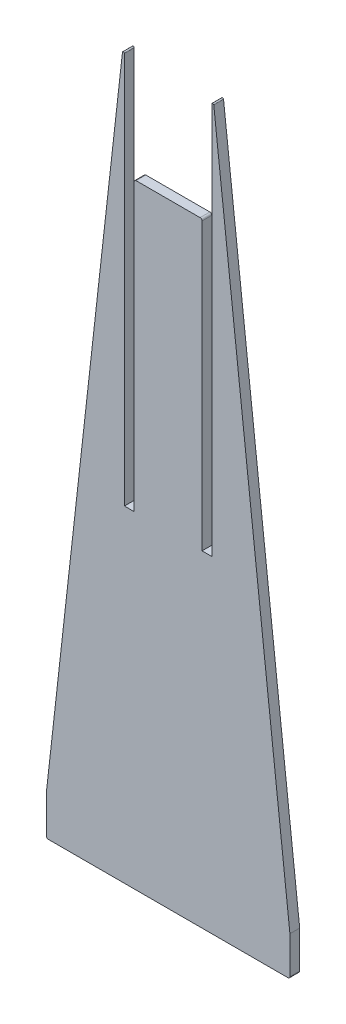
SolidWorks part; units mm, degrees
ref_plane "Front Plane" through (0, 0, 0) normal (0, 0, 1) x (1, 0, 0)
ref_plane "Top Plane" through (0, 0, 0) normal (0, 1, 0) x (1, 0, 0)
ref_plane "Right Plane" through (0, 0, 0) normal (1, 0, 0) x (0, 0, -1)
sketch "Sketch1" plane through (0, 0, 0) normal (0, 0, 1) x (1, 0, 0)
  line L0 (17.35, 0) -> (17.35, 20)
  line L1 (17.35, 0) -> (17.35, 20)
  line L2 (17.35, 20) -> (17.35, 195)
  line L3 (17.35, 20) -> (17.35, 195)
  line L4 (13.75, 450.8) -> (-13.75, 450.8)
  line L5 (-15.75, 448.8) -> (-15.75, 331.2)
  line L6 (-13.75, 329.2) -> (13.75, 329.2)
  line L7 (15.75, 331.2) -> (15.75, 448.8)
  line L8 (13.75, 450.8) -> (-13.75, 450.8)
  line L9 (-15.75, 448.8) -> (-15.75, 331.2)
  line L10 (-13.75, 329.2) -> (13.75, 329.2)
  line L11 (15.75, 331.2) -> (15.75, 448.8)
  line L12 (17.35, 195) -> (17.35, 390)
  line L13 (17.35, 195) -> (17.35, 390)
  line L14 (17.35, 390) -> (17.35, 406.6)
  line L15 (17.35, 390) -> (17.35, 406.6)
  line L16 (17.35, 406.6) -> (22.35, 406.6)
  line L17 (17.35, 406.6) -> (22.35, 406.6)
  line L18 (22.35, 406.6) -> (22.35, 390)
  line L19 (22.35, 406.6) -> (22.35, 390)
  line L20 (22.35, 390) -> (22.35, 195)
  line L21 (22.35, 390) -> (22.35, 195)
  line L22 (22.35, 195) -> (22.35, 20)
  line L23 (22.35, 195) -> (22.35, 20)
  line L24 (22.35, 20) -> (22.35, 0)
  line L25 (22.35, 20) -> (22.35, 0)
  line L26 (22.35, 0) -> (17.35, 0)
  line L27 (22.35, 0) -> (17.35, 0)
  line L28 (-22.35, 0) -> (-22.35, 20)
  line L29 (-22.35, 0) -> (-22.35, 20)
  line L30 (-22.35, 20) -> (-22.35, 195)
  line L31 (-22.35, 20) -> (-22.35, 195)
  line L32 (-22.35, 195) -> (-22.35, 390)
  line L33 (-22.35, 195) -> (-22.35, 390)
  line L34 (-22.35, 390) -> (-22.35, 406.6)
  line L35 (-22.35, 390) -> (-22.35, 406.6)
  line L36 (-22.35, 406.6) -> (-17.35, 406.6)
  line L37 (-22.35, 406.6) -> (-17.35, 406.6)
  line L38 (-17.35, 406.6) -> (-17.35, 390)
  line L39 (-17.35, 406.6) -> (-17.35, 390)
  line L40 (-17.35, 390) -> (-17.35, 195)
  line L41 (-17.35, 390) -> (-17.35, 195)
  line L42 (-17.35, 195) -> (-17.35, 20)
  line L43 (-17.35, 195) -> (-17.35, 20)
  line L44 (-17.35, 20) -> (-17.35, 0)
  line L45 (-17.35, 20) -> (-17.35, 0)
  line L46 (-17.35, 0) -> (-22.35, 0)
  line L47 (-17.35, 0) -> (-22.35, 0)
  line L48 (62.3, 20) -> (-62.3, 20) construction
  line L49 (62.3, 20) -> (-62.3, 20)
  line L50 (62.3, 0) -> (-62.3, 0) construction
  line L51 (62.3, 0) -> (-62.3, 0)
  line L52 (-75, 10.5) -> (-75, 0) construction
  line L53 (-75, 10.5) -> (-75, 0)
  line L54 (75, 0) -> (75, 10.5) construction
  line L55 (75, 0) -> (75, 10.5)
  line L56 (-16.25, 397.7) -> (-16.25, 382.3)
  line L57 (-16.25, 397.7) -> (-16.25, 382.3)
  line L58 (-16.25, 382.3) -> (-17.05, 381.5)
  line L59 (-16.25, 382.3) -> (-17.05, 381.5)
  line L60 (-17.05, 381.5) -> (-21.55, 381.5)
  line L61 (-17.05, 381.5) -> (-21.55, 381.5)
  line L62 (-21.55, 381.5) -> (-22.35, 382.3)
  line L63 (-21.55, 381.5) -> (-22.35, 382.3)
  line L64 (-22.35, 382.3) -> (-22.35, 397.7)
  line L65 (-22.35, 382.3) -> (-22.35, 397.7)
  line L66 (-22.35, 397.7) -> (-21.55, 398.5)
  line L67 (-22.35, 397.7) -> (-21.55, 398.5)
  line L68 (-21.55, 398.5) -> (-17.05, 398.5)
  line L69 (-21.55, 398.5) -> (-17.05, 398.5)
  line L70 (-17.05, 398.5) -> (-16.25, 397.7)
  line L71 (-17.05, 398.5) -> (-16.25, 397.7)
  line L72 (22.35, 397.7) -> (22.35, 382.3)
  line L73 (22.35, 397.7) -> (22.35, 382.3)
  line L74 (22.35, 382.3) -> (21.55, 381.5)
  line L75 (22.35, 382.3) -> (21.55, 381.5)
  line L76 (21.55, 381.5) -> (17.05, 381.5)
  line L77 (21.55, 381.5) -> (17.05, 381.5)
  line L78 (17.05, 381.5) -> (16.25, 382.3)
  line L79 (17.05, 381.5) -> (16.25, 382.3)
  line L80 (16.25, 382.3) -> (16.25, 397.7)
  line L81 (16.25, 382.3) -> (16.25, 397.7)
  line L82 (16.25, 397.7) -> (17.05, 398.5)
  line L83 (16.25, 397.7) -> (17.05, 398.5)
  line L84 (17.05, 398.5) -> (21.55, 398.5)
  line L85 (17.05, 398.5) -> (21.55, 398.5)
  line L86 (21.55, 398.5) -> (22.35, 397.7)
  line L87 (21.55, 398.5) -> (22.35, 397.7)
  arc A4 (-13.75, 450.8) -> (-15.75, 448.8) centre (-13.75, 448.8) ccw
  arc A5 (-15.75, 331.2) -> (-13.75, 329.2) centre (-13.75, 331.2) ccw
  arc A6 (13.75, 329.2) -> (15.75, 331.2) centre (13.75, 331.2) ccw
  arc A7 (15.75, 448.8) -> (13.75, 450.8) centre (13.75, 448.8) ccw
  arc A8 (-13.75, 450.8) -> (-15.75, 448.8) centre (-13.75, 448.8) ccw
  arc A9 (-15.75, 331.2) -> (-13.75, 329.2) centre (-13.75, 331.2) ccw
  arc A10 (13.75, 329.2) -> (15.75, 331.2) centre (13.75, 331.2) ccw
  arc A11 (15.75, 448.8) -> (13.75, 450.8) centre (13.75, 448.8) ccw
  dimension "D1" = 0
sketch "Sketch3" plane through (0, 0, 0) normal (0, 0, 1) x (1, 0, 0)
  line L0 (-22.35, 376.5) -> (-62.3, 20)
  line L1 (-22.35, 195) -> (-22.35, 390) construction
  line L2 (62.3, 20) -> (-62.3, 20) construction
  line L3 (-22.35, 20) -> (-22.35, 195) construction
  line L4 (-17.05, 381.5) -> (-21.55, 381.5) construction
  line L5 (-17.35, 314.2) -> (17.35, 314.2)
  line L6 (-17.35, 390) -> (-17.35, 195) construction
  line L7 (17.35, 195) -> (17.35, 390) construction
  line L8 (-13.75, 329.2) -> (13.75, 329.2) construction
  line L9 (-62.3, 20) -> (-62.3, 0)
  line L10 (62.3, 0) -> (-62.3, 0) construction
  line L11 (-62.3, 0) -> (62.3, 0)
  line L12 (-22.35, 376.5) -> (-22.35, 167.1)
  line L13 (-17.35, 314.2) -> (-17.35, 167.1)
  line L14 (-17.35, 195) -> (-17.35, 20) construction
  line L15 (17.35, 314.2) -> (17.35, 167.1)
  line L16 (0, 314.2) -> (0, 20) construction
  line L17 (-22.35, 167.1) -> (-17.35, 167.1)
  line L18 (22.35, 167.1) -> (17.35, 167.1)
  line L19 (22.35, 376.5) -> (22.35, 167.1)
  line L20 (22.35, 376.5) -> (62.3, 20)
  line L21 (62.3, 20) -> (62.3, 0)
  point P22 (0, 0)
  point P34 (0, 167.1)
  dimension "D2" = 5
  dimension "D3" = 15
extrude "Boss-Extrude1" add sketch "Sketch3" along normal mid plane 5
fillet "Fillet1" radius 1 4 edges at (-62.3, 0, 0) (62.3, 0, 0) (17.35, 314.2, 0) (-17.35, 314.2, 0)
fillet "Fillet2" radius 0.5 2 edges at (-22.35, 376.5, 0) (22.35, 376.5, 0)
equation "\"Black_acrylic\"= 1.35mm"
equation "\"MDF_base\"= 20mm"
equation "\"Supports_material\"= 5mm"
